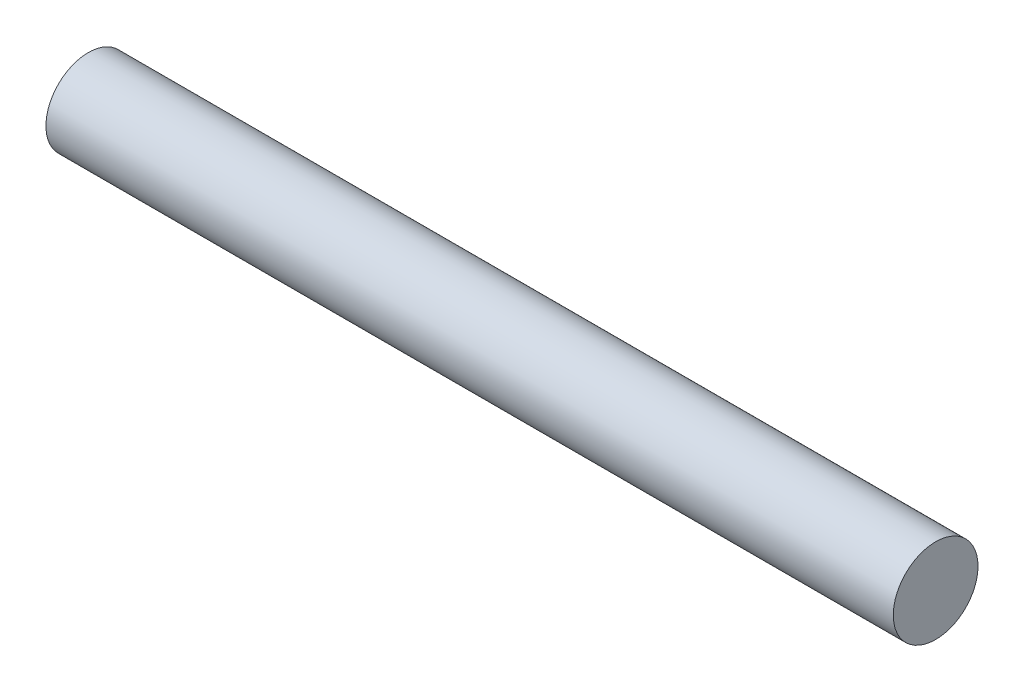
SolidWorks part; units mm, degrees
ref_plane "Front Plane" through (0, 0, 0) normal (0, 0, 1) x (1, 0, 0)
ref_plane "Top Plane" through (0, 0, 0) normal (0, 1, 0) x (1, 0, 0)
ref_plane "Right Plane" through (0, 0, 0) normal (1, 0, 0) x (0, 0, -1)
sketch "Sketch2" plane through (0, 0, 0) normal (1, 0, 0) x (0, 0, -1)
  circle A0 centre (0, 0) radius 2.5
extrude "Boss-Extrude1" add sketch "Sketch2" along normal blind 50
